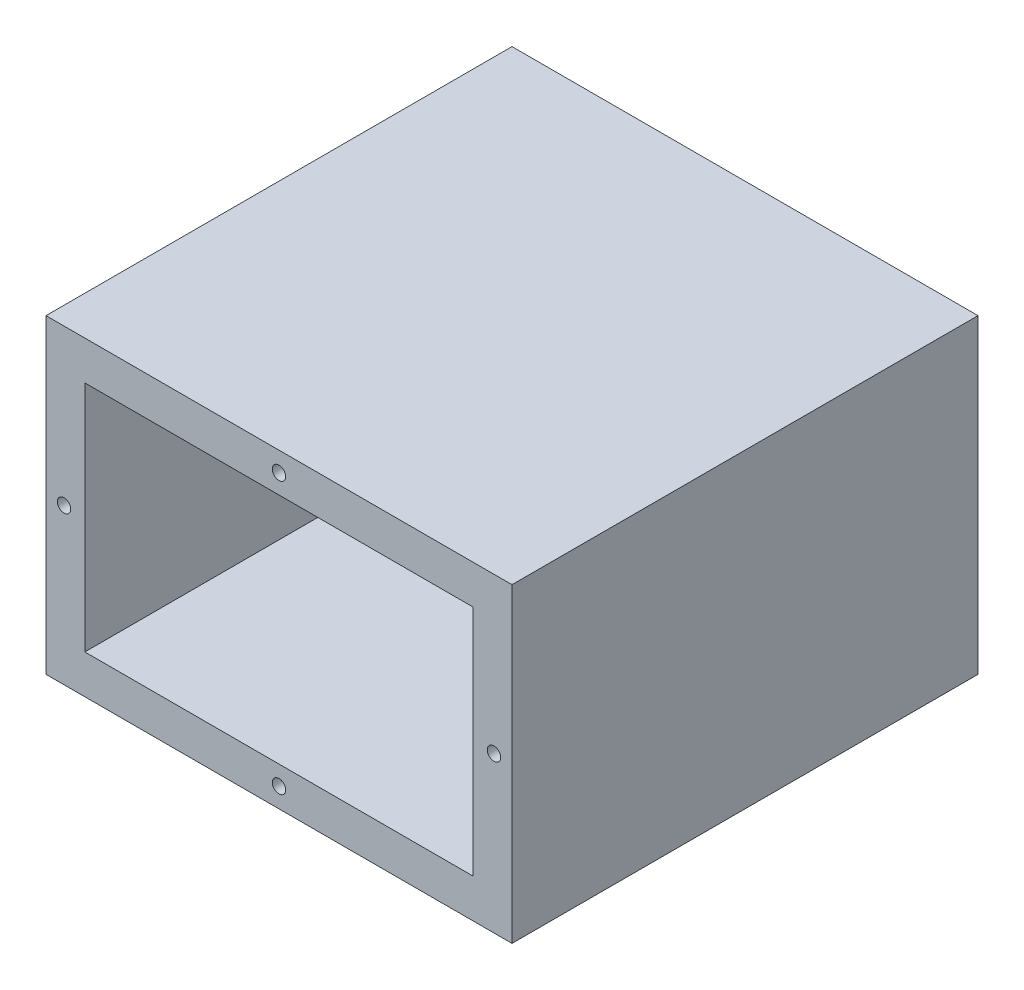
SolidWorks part; units mm, degrees
material "Alloy Steel"
ref_plane "Front Plane" through (0, 0, 0) normal (0, 0, 1) x (1, 0, 0)
ref_plane "Top Plane" through (0, 0, 0) normal (0, 1, 0) x (1, 0, 0)
ref_plane "Right Plane" through (0, 0, 0) normal (1, 0, 0) x (0, 0, -1)
sketch "Sketch1" plane through (0, 0, 0) normal (0, 0, 1) x (1, 0, 0)
  line L1 (38.1, -25.4) -> (-38.1, -25.4)
  line L2 (38.1, -25.4) -> (38.1, 25.4)
  line L3 (38.1, 25.4) -> (-38.1, 25.4)
  line L4 (-38.1, -25.4) -> (-38.1, 25.4)
  line L5 (38.1, -25.4) -> (-38.1, 25.4) construction
  line L6 (38.1, 25.4) -> (-38.1, -25.4) construction
  point P0 (0, 0)
  dimension "D1" = 76.2
  dimension "D2" = 50.8
extrude "Boss-Extrude1" add sketch "Sketch1" along normal blind 76.2
sketch "Sketch2" plane through (0, 0, 76.2) normal (0, 0, 1) x (1, 0, 0)
  line L0 (-38.1, 25.4) -> (-38.1, -25.4) construction
  line L1 (31.75, -19.05) -> (-31.75, -19.05)
  line L2 (31.75, -19.05) -> (31.75, 19.05)
  line L3 (31.75, 19.05) -> (-31.75, 19.05)
  line L4 (-31.75, -19.05) -> (-31.75, 19.05)
  line L5 (31.75, -19.05) -> (-31.75, 19.05) construction
  line L6 (31.75, 19.05) -> (-31.75, -19.05) construction
  line L7 (38.1, 25.4) -> (-38.1, 25.4) construction
  point P0 (0, 0)
  dimension "D1" = 6.35
  dimension "D2" = 6.35
extrude "Cut-Extrude1" cut sketch "Sketch2" against normal blind 71.12
sketch "Sketch3" plane through (0, 0, 5.08) normal (0, 0, 1) x (1, 0, 0)
  line L0 (-38.1, 0) -> (38.1, 0) construction
  line L1 (-38.1, 25.4) -> (-38.1, -25.4) construction
  line L2 (38.1, -25.4) -> (38.1, 25.4) construction
  circle A0 centre (0, 0) radius 3.175
  circle A1 centre (-16.51, 0) radius 1.651
  dimension "D1" = 16.51
  dimension "D2" = 3.302
  dimension "D3" = 6.35
extrude "Cut-Extrude2" cut sketch "Sketch3" against normal blind 48.26
sketch "Sketch4" plane through (0, 0, 76.2) normal (0, 0, 1) x (1, 0, 0)
  line L0 (-38.1, 0) -> (38.1, 0) construction
  line L1 (-38.1, 25.4) -> (-38.1, -25.4) construction
  line L2 (38.1, -25.4) -> (38.1, 25.4) construction
  line L3 (0, -25.4) -> (0, 25.4) construction
  line L4 (-38.1, -25.4) -> (38.1, -25.4) construction
  line L5 (38.1, 25.4) -> (-38.1, 25.4) construction
  circle A0 centre (-35.1498, 0) radius 1.0922
  circle A1 centre (35.1498, 0) radius 1.0922
  circle A2 centre (0, 22.1865) radius 1.0922
  circle A3 centre (0, -22.1865) radius 1.0922
  dimension "D1" = 2.1844
  dimension "D2" = 2.1844
extrude "Cut-Extrude3" cut sketch "Sketch4" against normal blind 15.875
